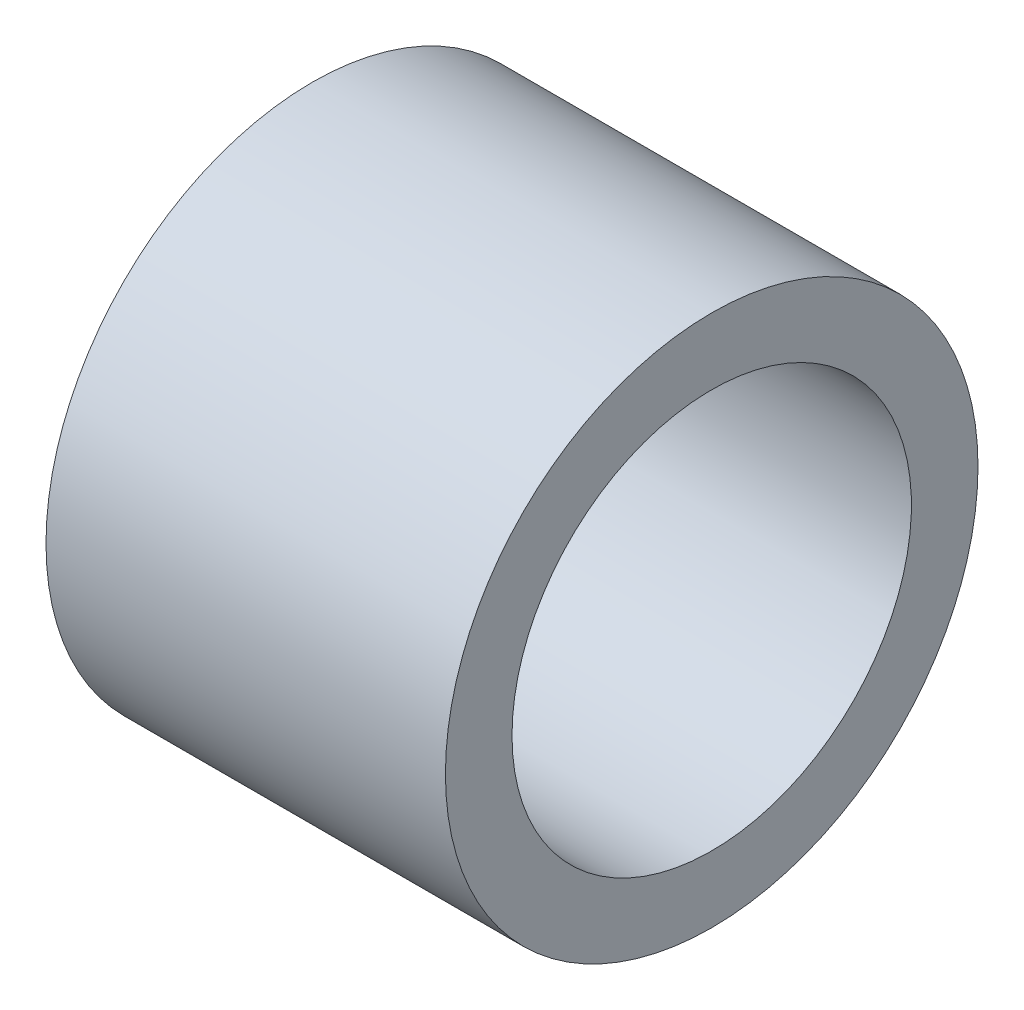
SolidWorks part; units mm, degrees
ref_plane "Front Plane" through (0, 0, 0) normal (0, 0, 1) x (1, 0, 0)
ref_plane "Top Plane" through (0, 0, 0) normal (0, 1, 0) x (1, 0, 0)
ref_plane "Right Plane" through (0, 0, 0) normal (1, 0, 0) x (0, 0, -1)
sketch "Sketch3" plane through (0, 0, 0) normal (1, 0, 0) x (0, 0, -1)
  circle A0 centre (0, 0) radius 9.525
  circle A1 centre (0, 0) radius 12.7
  dimension "D1" = 19.05
  dimension "D2" = 25.4
extrude "Boss-Extrude1" add sketch "Sketch3" along normal mid plane 19.05
